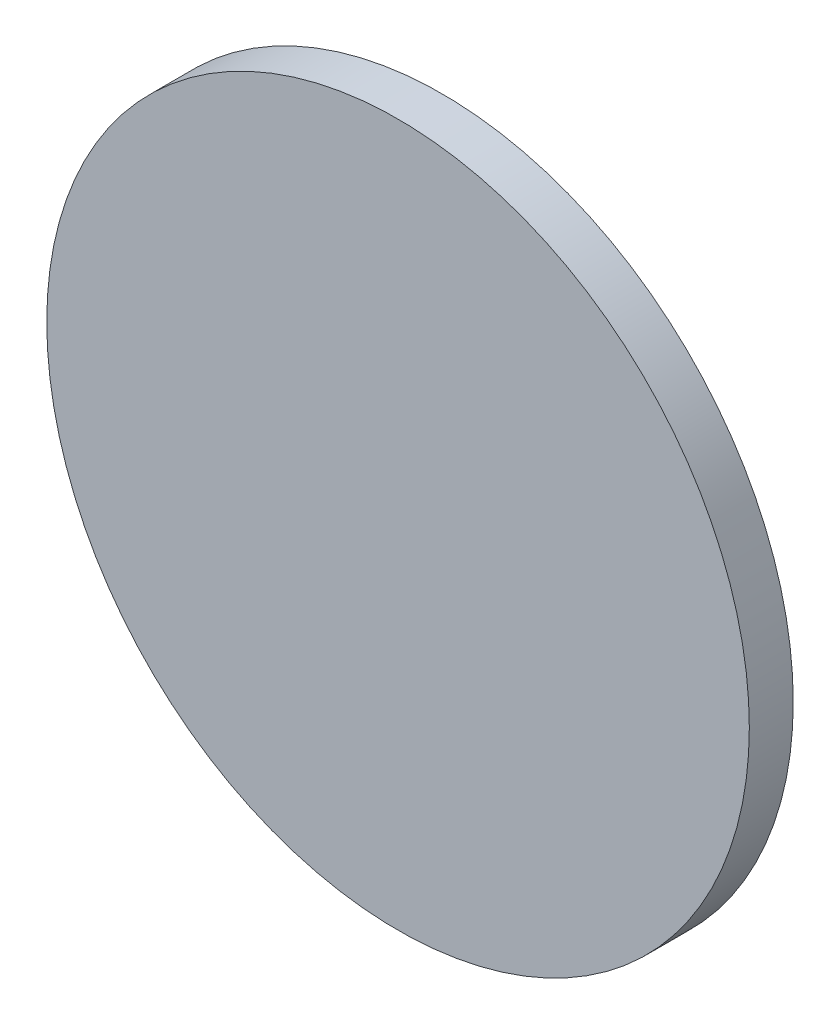
SolidWorks part; units mm, degrees
ref_plane "Front Plane" through (0, 0, 0) normal (0, 0, 1) x (1, 0, 0)
ref_plane "Top Plane" through (0, 0, 0) normal (0, 1, 0) x (1, 0, 0)
ref_plane "Right Plane" through (0, 0, 0) normal (1, 0, 0) x (0, 0, -1)
sketch "Sketch1" plane through (0, 0, 0) normal (0, 0, 1) x (1, 0, 0)
  circle A0 centre (0, 0) radius 50.8
  dimension "D1" = 101.6
extrude "Boss-Extrude1" add sketch "Sketch1" along normal blind 6.35
